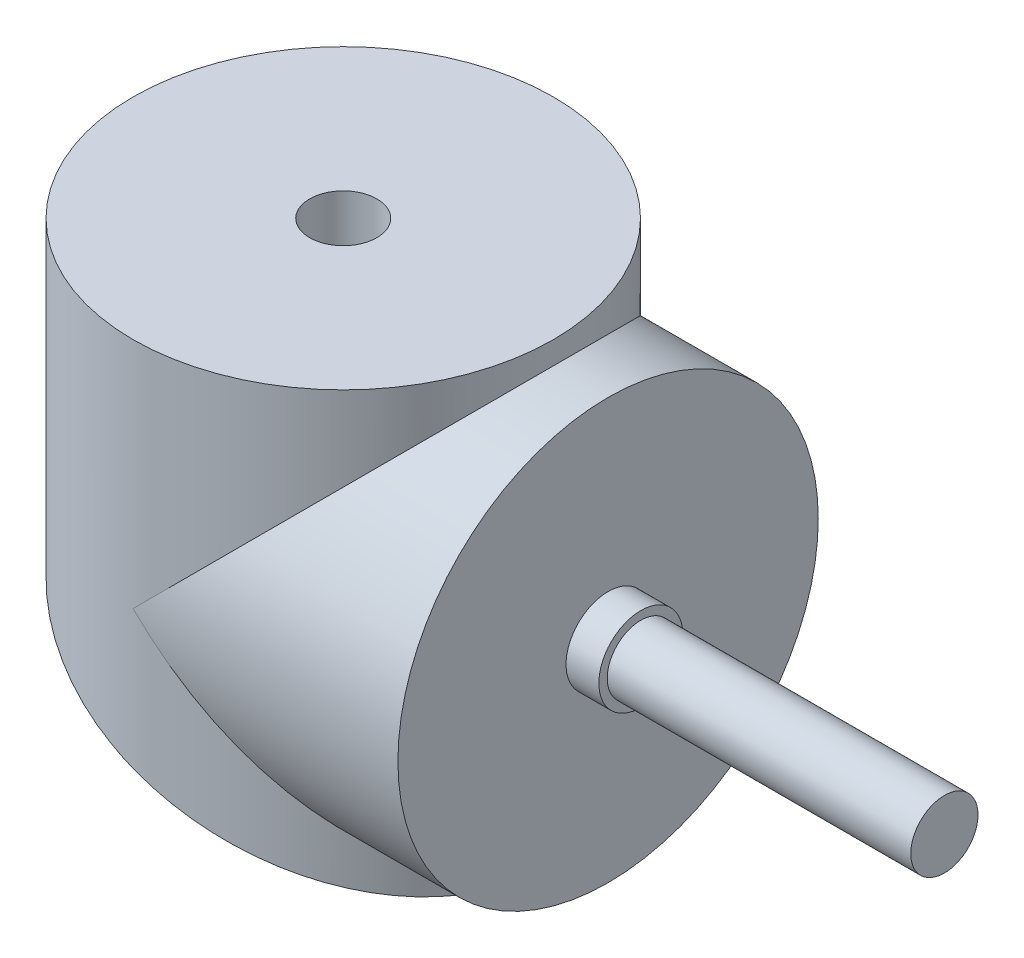
SolidWorks part; units mm, degrees
ref_plane "Front Plane" through (0, 0, 0) normal (0, 0, 1) x (1, 0, 0)
ref_plane "Top Plane" through (0, 0, 0) normal (0, 1, 0) x (1, 0, 0)
ref_plane "Right Plane" through (0, 0, 0) normal (1, 0, 0) x (0, 0, -1)
sketch "Sketch1" plane through (0, 0, 0) normal (1, 0, 0) x (0, 0, -1)
  circle A0 centre (0, 0) radius 37.5
  dimension "D1" = 75
extrude "Boss-Extrude1" add sketch "Sketch1" along normal blind 47.25
sketch "Sketch2" plane through (0, 0, 0) normal (0, 1, 0) x (1, 0, 0)
  circle A0 centre (0, 0) radius 37.5
  dimension "D1" = 75
extrude "Boss-Extrude2" add sketch "Sketch2" along normal blind 41.55 and the other way blind 39.7046
sketch "Sketch3" plane through (0, 0, 0) normal (0, 0, 1) x (1, 0, 0)
  line L0 (37.5, -39.7046) -> (-37.5, -39.7046)
  line L1 (-37.5, -39.7046) -> (-37.5, -9.7046)
  line L2 (-37.5, 41.55) -> (-37.5, -39.7046) construction
  line L3 (-37.5, -9.7046) -> (37.5, -39.7046)
  dimension "D1" = 21.801
extrude "Cut-Extrude1" cut sketch "Sketch3" against normal through all both and the other way through all
sketch "Sketch4" plane through (47.25, 0, 0) normal (1, 0, 0) x (0, 0, -1)
  circle A0 centre (0, 0) radius 6
  dimension "D1" = 12
extrude "Boss-Extrude3" add sketch "Sketch4" along normal blind 60
sketch "Sketch5" plane through (47.25, 0, 0) normal (1, 0, 0) x (0, 0, -1)
  circle A0 centre (0, 0) radius 7.5
  dimension "D1" = 15
extrude "Boss-Extrude4" add sketch "Sketch5" along normal blind 5.85
sketch "Sketch6" plane through (0, 41.55, 0) normal (0, 1, 0) x (1, 0, 0)
  circle A0 centre (0, 0) radius 6
  dimension "D1" = 12
extrude "Cut-Extrude2" cut sketch "Sketch6" against normal blind 58.15 and the other way through all
